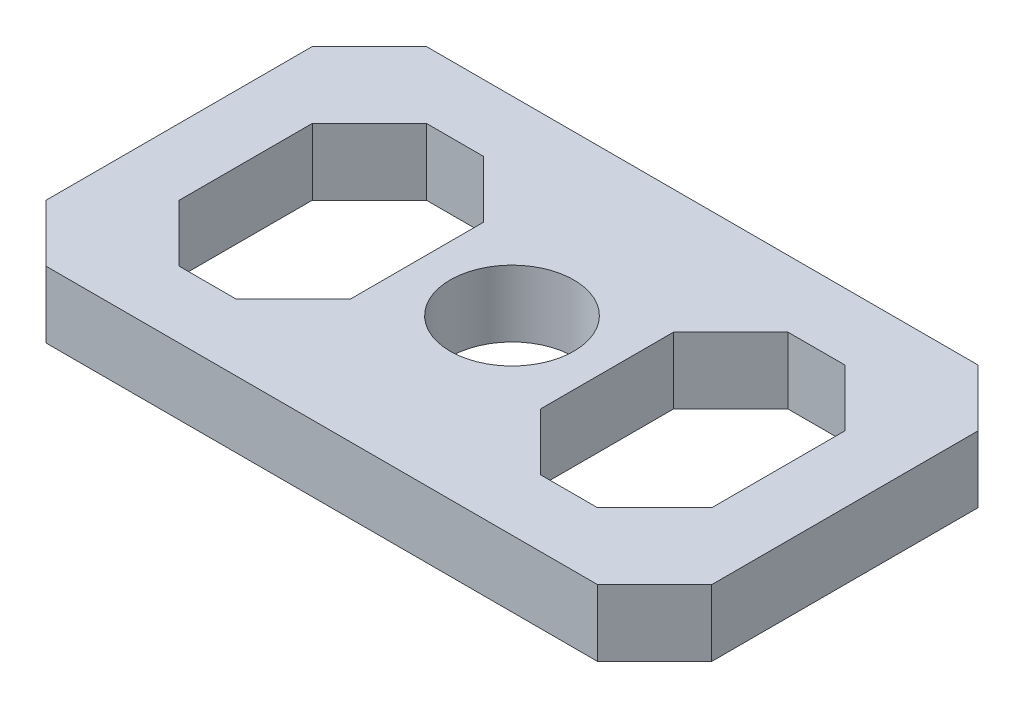
SolidWorks part; units mm, degrees
ref_plane "Front Plane" through (0, 0, 0) normal (0, 0, 1) x (1, 0, 0)
ref_plane "Top Plane" through (0, 0, 0) normal (0, 1, 0) x (1, 0, 0)
ref_plane "Right Plane" through (0, 0, 0) normal (1, 0, 0) x (0, 0, -1)
sketch "Sketch1" plane through (0, 0, 0) normal (0, 1, 0) x (1, 0, 0)
  line L0 (-41.3491, 0) -> (50.6776, 0) construction
  line L1 (-35, 20) -> (35, 20)
  line L2 (-35, 20) -> (-35, -20)
  line L3 (-35, -20) -> (35, -20)
  line L4 (35, 20) -> (35, -20)
  line L5 (-35, 20) -> (35, -20) construction
  line L6 (-35, -20) -> (35, 20) construction
  line L8 (-28, 13) -> (-10, 13)
  line L9 (-28, 13) -> (-28, -13)
  line L10 (-28, -13) -> (-10, -13)
  line L11 (-10, 13) -> (-10, -13)
  line L12 (-28, 13) -> (-10, -13) construction
  line L13 (-28, -13) -> (-10, 13) construction
  line L14 (10, 13) -> (28, 13)
  line L15 (10, 13) -> (10, -13)
  line L16 (10, -13) -> (28, -13)
  line L17 (28, 13) -> (28, -13)
  line L18 (10, 13) -> (28, -13) construction
  line L19 (10, -13) -> (28, 13) construction
  circle A0 centre (0, 0) radius 6.5
  point P9 (-19, 0)
  point P14 (19, 0)
  dimension "D1" = 13
  dimension "D2" = 70
  dimension "D3" = 40
  dimension "D4" = 7
  dimension "D6" = 7
  dimension "D7" = 10
  dimension "D8" = 7
extrude "Boss-Extrude1" add sketch "Sketch1" along normal blind 7
chamfer "Chamfer1" distance 6 angle 45 12 edges at (-35, 3.5, -20) (-35, 3.5, 20) (-28, 3.5, -13) (-10, 3.5, -13) (-10, 3.5, 13) (-28, 3.5, 13) (10, 3.5, 13) (28, 3.5, 13) (28, 3.5, -13) (10, 3.5, -13) (35, 3.5, 20) (35, 3.5, -20)
